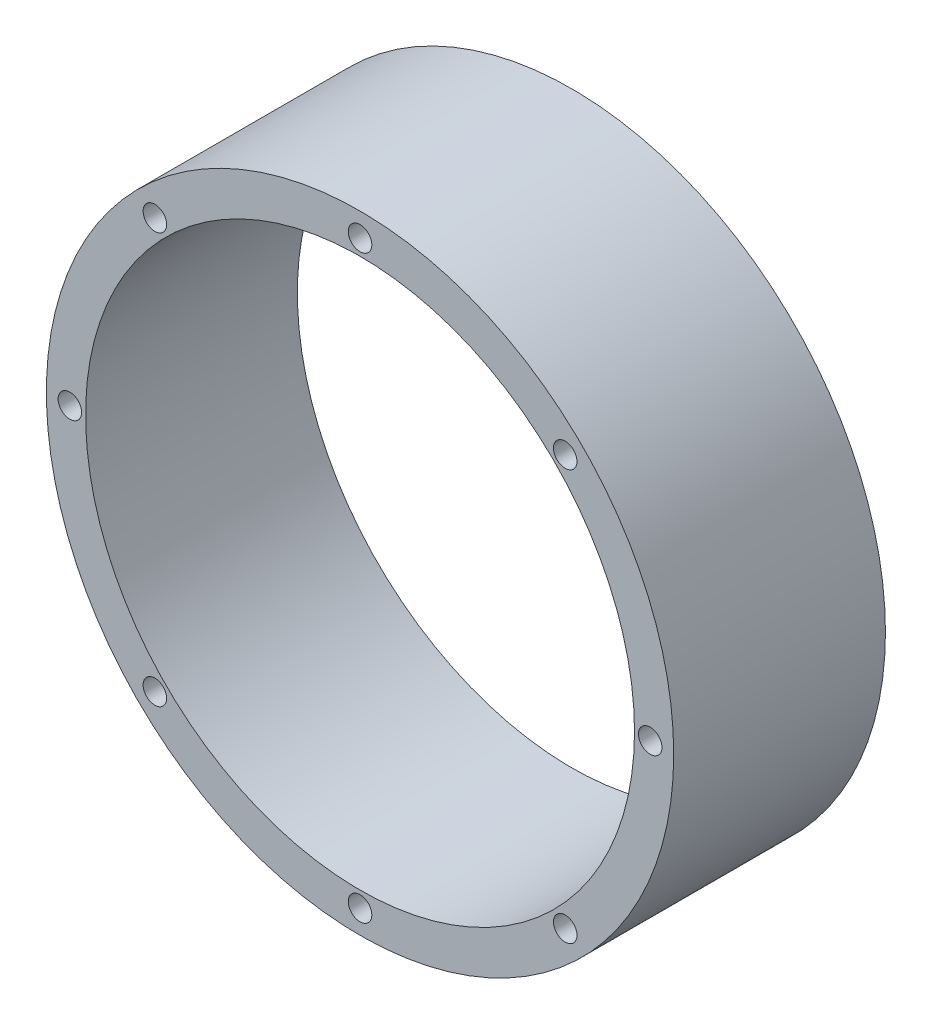
SolidWorks part; units mm, degrees
ref_plane "Front Plane" through (0, 0, 0) normal (0, 0, 1) x (1, 0, 0)
ref_plane "Top Plane" through (0, 0, 0) normal (0, 1, 0) x (1, 0, 0)
ref_plane "Right Plane" through (0, 0, 0) normal (1, 0, 0) x (0, 0, -1)
sketch "Sketch1" plane through (0, 0, 0) normal (0, 0, 1) x (1, 0, 0)
  line L0 (0, 0) -> (0, 48.3665) construction
  circle A0 centre (0, 0) radius 40
  circle A1 centre (0, 0) radius 35
  point P0 (0, 0)
  point P5 (0, 37)
  point P10 (26.163, 26.163)
  point P11 (37, 0)
  point P12 (26.163, -26.163)
  point P13 (0, -37)
  point P14 (-26.163, -26.163)
  point P15 (-37, 0)
  point P16 (-26.163, 26.163)
  point P17 (0, 0)
  dimension "D1" = 80
  dimension "D2" = 70
  dimension "D3" = 37
  dimension "D4" = 8
extrude "Boss-Extrude1" add sketch "Sketch1" along normal blind 27
sketch "Sketch2" plane through (0, 0, 0) normal (0, 0, 1) x (1, 0, 0)
  line L0 (0, 0) -> (0, 48.3665) construction
  circle A0 centre (0, 0) radius 40
  circle A1 centre (0, 0) radius 35
  point P0 (0, 0)
  point P5 (0, 37)
  point P10 (26.163, 26.163)
  point P11 (37, 0)
  point P12 (26.163, -26.163)
  point P13 (0, -37)
  point P14 (-26.163, -26.163)
  point P15 (-37, 0)
  point P16 (-26.163, 26.163)
  point P17 (0, 0)
  dimension "D1" = 80
  dimension "D2" = 70
  dimension "D3" = 37
  dimension "D4" = 8
hole_wizard "Ø3.0mm Dowel Hole1" positions "Sketch3" profile "Sketch4" hole size "Ø3.0" standard "ISO" end condition through all
sketch "Sketch3" plane through (0, 0, 0) normal (0, 0, -1) x (-1, 0, 0)
  point P0 (0, 37)
  point P3 (26.163, 26.163)
  point P6 (37, 0)
  point P9 (-26.163, 26.163)
  point P12 (-37, 0)
  point P15 (-26.163, -26.163)
  point P18 (0, -37)
  point P21 (26.163, -26.163)
sketch "Sketch4" plane through (0, 37, 0) normal (1, 0, 0) x (0, 1, 0)
  line L0 (0, 0) -> (0, 27)
  line L1 (0, 27) -> (1.5, 27)
  line L2 (1.5, 27) -> (1.5, 0.025)
  line L3 (1.5, 0.025) -> (1.525, 0)
  line L5 (1.525, 0) -> (0, 0)
  line L6 (-1.5, 0.025) -> (-1.525, 0) construction
  line L11 (0, -6.35) -> (0, 107.95) construction
  dimension "Thru Hole Dia." = 3
  dimension "Thru Hole Depth" = 27
  dimension "Near C'Sink Dia." = 3.05
  dimension "Near C'Sink Angle" = 90
